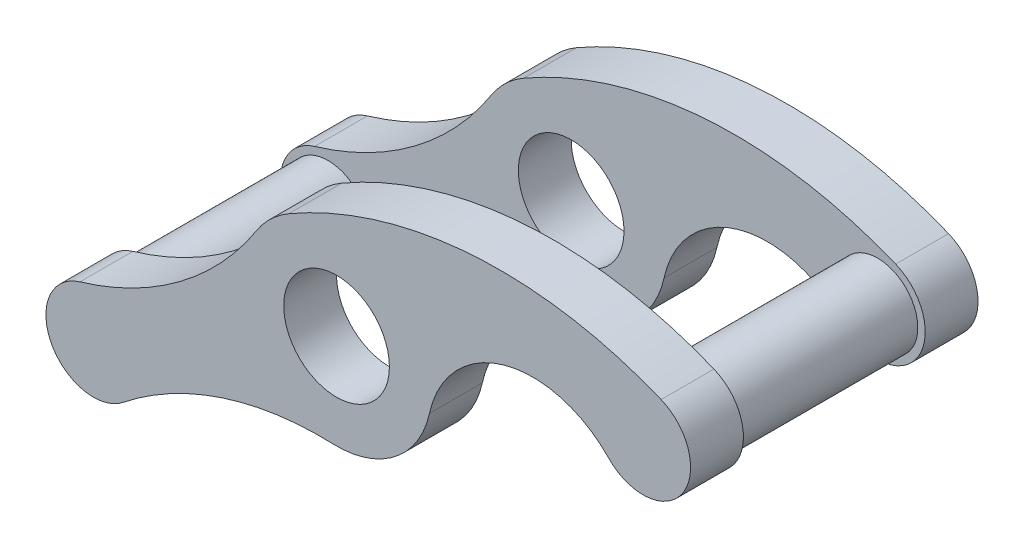
SolidWorks part; units mm, degrees
ref_plane "Alzado" through (0, 0, 0) normal (0, 0, 1) x (1, 0, 0)
ref_plane "Planta" through (0, 0, 0) normal (0, 1, 0) x (1, 0, 0)
ref_plane "Vista lateral" through (0, 0, 0) normal (1, 0, 0) x (0, 0, -1)
sketch "Croquis1" plane through (0, 0, 0) normal (0, 0, 1) x (1, 0, 0)
  circle A0 centre (0, 0) radius 2.5
  arc A1 (-0.1717, -4.4967) -> (4.3959, -0.9623) centre (0, 0) ccw
  arc A2 (12.8801, 1.4385) -> (15.3547, 5.0813) centre (14.5, 3) ccw
  arc A5 (-12.1402, -3.843) -> (-10.097, -7.759) centre (-11.5, -6) ccw
  arc A6 (-12.1402, -3.843) -> (-3.7864, 2.4316) centre (-16.4079, 10.5371) ccw
  arc A7 (-0.1717, -4.4967) -> (-10.097, -7.759) centre (-0.7438, -19.4858) ccw
  arc A8 (15.3547, 5.0813) -> (-2.252, 3.8959) centre (7.757, -13.4193) ccw
  arc A9 (12.8801, 1.4385) -> (4.3959, -0.9623) centre (9.2802, -2.0316) ccw
  arc A10 (-2.252, 3.8959) -> (-3.7864, 2.4316) centre (0, 0) ccw
  dimension "D1" = 5
  dimension "D2" = 9
  dimension "D3" = 14.5
  dimension "D5" = 4.5
  dimension "D7" = 11.5
  dimension "D9" = 4.5
  dimension "D11" = 30
  dimension "D12" = 30
  dimension "D13" = 40
  dimension "D14" = 10
  dimension "D4" = 3
  dimension "D8" = 6
extrude "Saliente-Extruir1" add sketch "Croquis1" along normal blind 2.5
sketch "Croquis2" plane through (0, 0, 2.5) normal (0, 0, 1) x (1, 0, 0)
  circle A0 centre (-11.5, -6) radius 1.9
  circle A1 centre (14.5, 3) radius 1.9
  dimension "D1" = 3.8
extrude "Saliente-Extruir2" add sketch "Croquis2" along normal blind 8.6
sketch "Croquis3" plane through (0, 0, 11.1) normal (0, 0, 1) x (1, 0, 0)
  circle A0 centre (0, 0) radius 2.5 construction
  arc A1 (12.8801, 1.4385) -> (15.3547, 5.0813) centre (14.5, 3) ccw construction
  arc A2 (12.8801, 1.4385) -> (4.3959, -0.9623) centre (9.2802, -2.0316) ccw construction
  arc A3 (-0.1717, -4.4967) -> (4.3959, -0.9623) centre (0, 0) ccw construction
  arc A4 (-0.1717, -4.4967) -> (-10.097, -7.759) centre (-0.7438, -19.4858) ccw construction
  arc A5 (-12.1402, -3.843) -> (-10.097, -7.759) centre (-11.5, -6) ccw construction
  arc A6 (15.3547, 5.0813) -> (-2.252, 3.8959) centre (7.757, -13.4193) ccw construction
  arc A7 (-2.252, 3.8959) -> (-3.7864, 2.4316) centre (0, 0) ccw construction
  arc A8 (-12.1402, -3.843) -> (-3.7864, 2.4316) centre (-16.4079, 10.5371) ccw construction
  circle A9 centre (0, 0) radius 2.5
  arc A10 (12.8801, 1.4385) -> (15.3547, 5.0813) centre (14.5, 3) ccw
  arc A11 (12.8801, 1.4385) -> (4.3959, -0.9623) centre (9.2802, -2.0316) ccw
  arc A12 (-0.1717, -4.4967) -> (4.3959, -0.9623) centre (0, 0) ccw
  arc A13 (-0.1717, -4.4967) -> (-10.097, -7.759) centre (-0.7438, -19.4858) ccw
  arc A14 (-12.1402, -3.843) -> (-10.097, -7.759) centre (-11.5, -6) ccw
  arc A15 (15.3547, 5.0813) -> (-2.252, 3.8959) centre (7.757, -13.4193) ccw
  arc A16 (-2.252, 3.8959) -> (-3.7864, 2.4316) centre (0, 0) ccw
  arc A17 (-12.1402, -3.843) -> (-3.7864, 2.4316) centre (-16.4079, 10.5371) ccw
extrude "Saliente-Extruir3" add sketch "Croquis3" along normal blind 2.5
